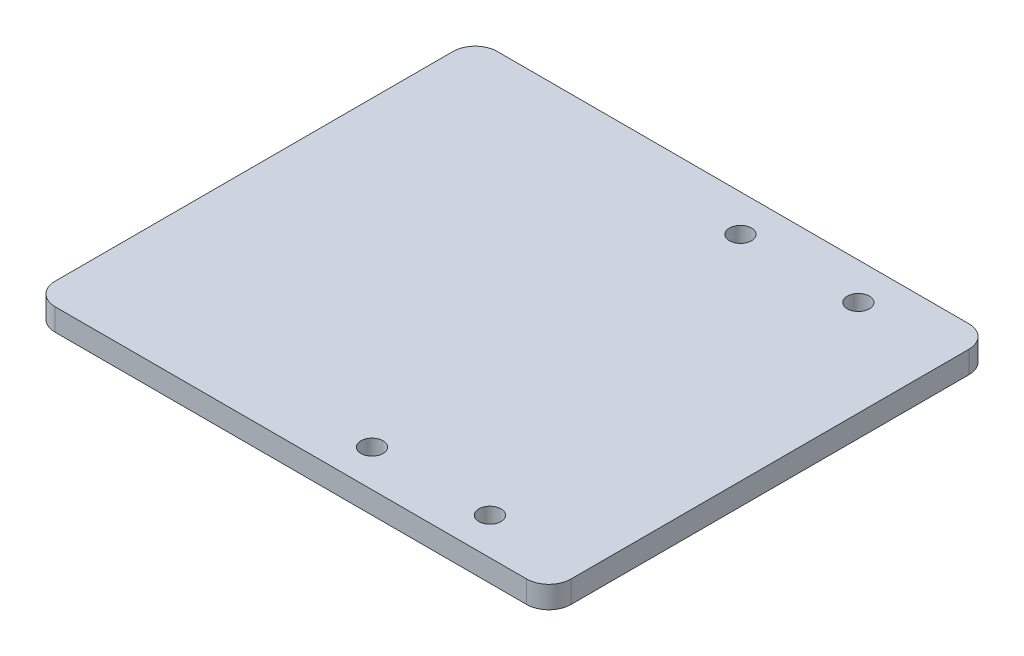
SolidWorks part; units mm, degrees
ref_plane "前视基准面" through (0, 0, 0) normal (0, 0, 1) x (1, 0, 0)
ref_plane "上视基准面" through (0, 0, 0) normal (0, 1, 0) x (1, 0, 0)
ref_plane "右视基准面" through (0, 0, 0) normal (1, 0, 0) x (0, 0, -1)
sketch "草图1" plane through (0, 0, 0) normal (0, 1, 0) x (1, 0, 0)
  line L1 (0, 0) -> (70, 0)
  line L2 (0, 0) -> (0, -60)
  line L3 (0, -60) -> (70, -60)
  line L4 (70, 0) -> (70, -60)
  dimension "D1" = 60
  dimension "D2" = 70
extrude "凸台-拉伸1" add sketch "草图1" along normal blind 3
sketch "草图2" plane through (0, 3, 0) normal (0, 1, 0) x (1, 0, 0)
  circle A0 centre (57, -5) radius 1.5
  circle A1 centre (41, -5) radius 1.5
  circle A2 centre (57, -55) radius 1.5
  circle A3 centre (41, -55) radius 1.5
  dimension "D1" = 3
extrude "切除-拉伸1" cut sketch "草图2" against normal through all
fillet "圆角1" radius 3 4 edges at (0, 1.5, 60) (0, 1.5, 0) (70, 1.5, 0) (70, 1.5, 60)
